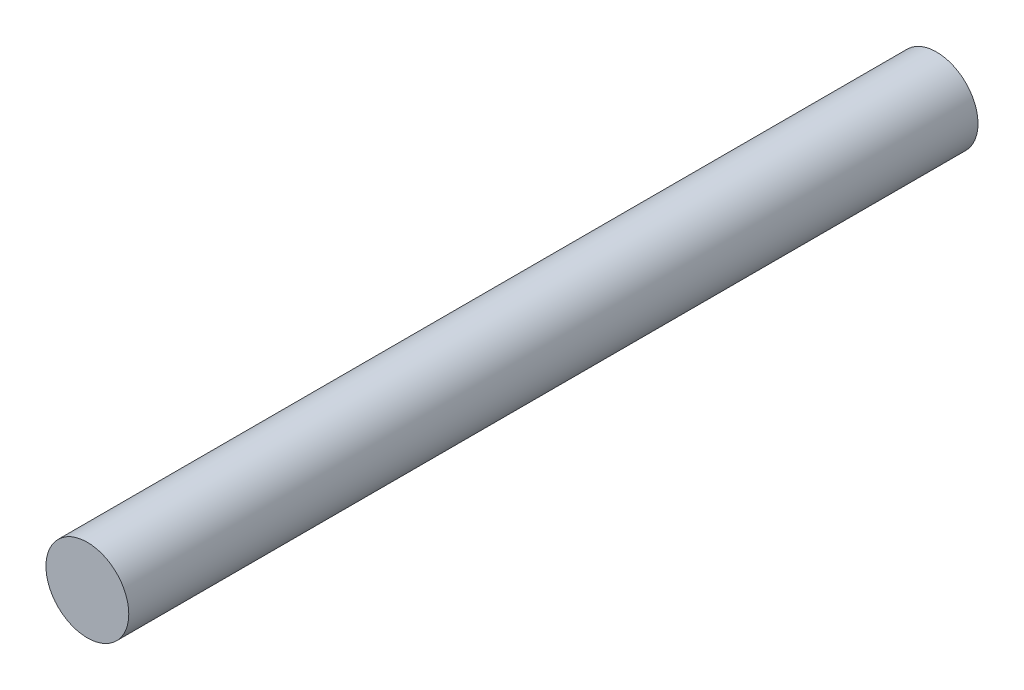
SolidWorks part; units mm, degrees
ref_plane "Plano frontal" through (0, 0, 0) normal (0, 0, 1) x (1, 0, 0)
ref_plane "Plano superior" through (0, 0, 0) normal (0, 1, 0) x (1, 0, 0)
ref_plane "Plano direito" through (0, 0, 0) normal (1, 0, 0) x (0, 0, -1)
sketch "Esboço1" plane through (0, 0, 0) normal (0, 0, 1) x (1, 0, 0)
  circle A0 centre (0, 0) radius 4
  dimension "D1" = 8
extrude "Ressalto-extrusão1" add sketch "Esboço1" along normal blind 82
cosmetic thread "Representação de rosca1" parameters "D2"=6.891
cosmetic thread "Representação de rosca2" parameters "D2"=6.891
cosmetic thread "Representação de rosca3" parameters "D2"=6.891
